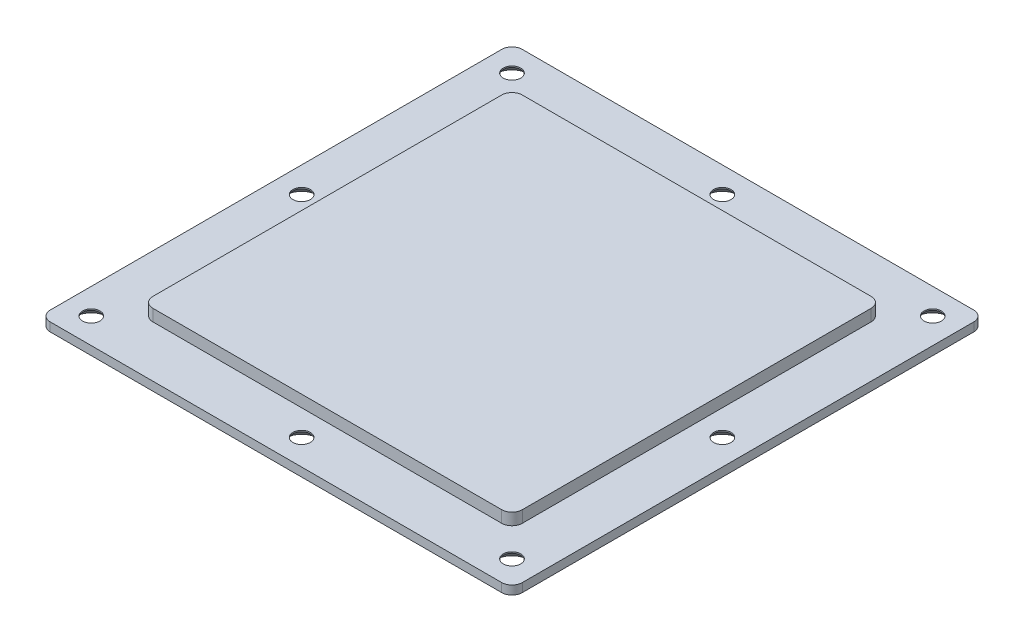
SolidWorks part; units mm, degrees
material "6061 Alloy"
ref_plane "Front Plane" through (0, 0, 0) normal (0, 0, 1) x (1, 0, 0)
ref_plane "Top Plane" through (0, 0, 0) normal (0, 1, 0) x (1, 0, 0)
ref_plane "Right Plane" through (0, 0, 0) normal (1, 0, 0) x (0, 0, -1)
sketch "Sketch1" plane through (0, 0, 0) normal (0, 1, 0) x (1, 0, 0)
  line L1 (-46, -46) -> (46, -46)
  line L2 (-46, -46) -> (-46, 46)
  line L3 (-46, 46) -> (46, 46)
  line L4 (46, -46) -> (46, 46)
  line L5 (-46, -46) -> (46, 46) construction
  line L6 (-46, 46) -> (46, -46) construction
  point P0 (0, 0)
  dimension "D1" = 92
extrude "Boss-Extrude1" add sketch "Sketch1" along normal mid plane 1.7
sketch "Sketch2" plane through (0, 0.85, 0) normal (0, 1, 0) x (1, 0, 0)
  line L1 (-36, -36) -> (36, -36)
  line L2 (-36, -36) -> (-36, 36)
  line L3 (-36, 36) -> (36, 36)
  line L4 (36, -36) -> (36, 36)
  line L5 (-36, -36) -> (36, 36) construction
  line L6 (-36, 36) -> (36, -36) construction
  point P0 (0, 0)
  dimension "D1" = 72
extrude "Boss-Extrude2" add sketch "Sketch2" along normal blind 2.3
sketch "Sketch3" plane through (0, -0.85, 0) normal (0, -1, 0) x (1, 0, 0)
  line L0 (0, 0) -> (-41, 0)
  line L1 (-41, -41) -> (41, -41)
  line L2 (-41, -41) -> (-41, 41)
  line L3 (-41, 41) -> (41, 41)
  line L4 (41, -41) -> (41, 41)
  line L5 (-41, -41) -> (41, 41) construction
  line L6 (-41, 41) -> (41, -41) construction
  line L7 (0, 0) -> (0, 41)
  line L8 (0, 0) -> (41, 0)
  line L9 (0, 0) -> (0, -41)
  line L10 (46, 46) -> (46, -46) construction
  point P0 (0, 0)
  dimension "D1" = 5
hole_wizard "CSK for M3 Flat Head Machine Screw1" positions "3DSketch1" profile "Sketch4" countersink size "M3" standard "ANSI Metric" end condition through all
sketch3d "3DSketch1"
  point P0 (-41, -0.85, 41)
  point P3 (0, -0.85, 41)
  point P6 (41, -0.85, 41)
  point P9 (41, -0.85, 0)
  point P12 (41, -0.85, -41)
  point P15 (0, -0.85, -41)
  point P18 (-41, -0.85, -41)
  point P21 (-41, -0.85, 0)
sketch "Sketch4" plane through (-41, -0.85, 41) normal (1, 0, 0) x (0, 0, -1)
  line L0 (0, 0) -> (0, 4)
  line L1 (0, 4) -> (1.7, 4)
  line L2 (1.7, 4) -> (1.7, 1.45)
  line L3 (1.7, 1.45) -> (3.15, 0)
  line L5 (3.15, 0) -> (0, 0)
  line L6 (-1.7, 1.45) -> (-3.15, 0) construction
  line L11 (0, -6.35) -> (0, 107.95) construction
  dimension "Thru Hole Dia." = 3.4
  dimension "Thru Hole Depth" = 4
  dimension "Near C'Sink Dia." = 6.3
  dimension "Near C'Sink Angle" = 90
fillet "Fillet1" radius 2 8 edges at (46, 0, 46) (-46, 0, -46) (46, 0, -46) (-46, 0, 46) (36, 2, -36) (-36, 2, -36) (36, 2, 36) (-36, 2, 36)
